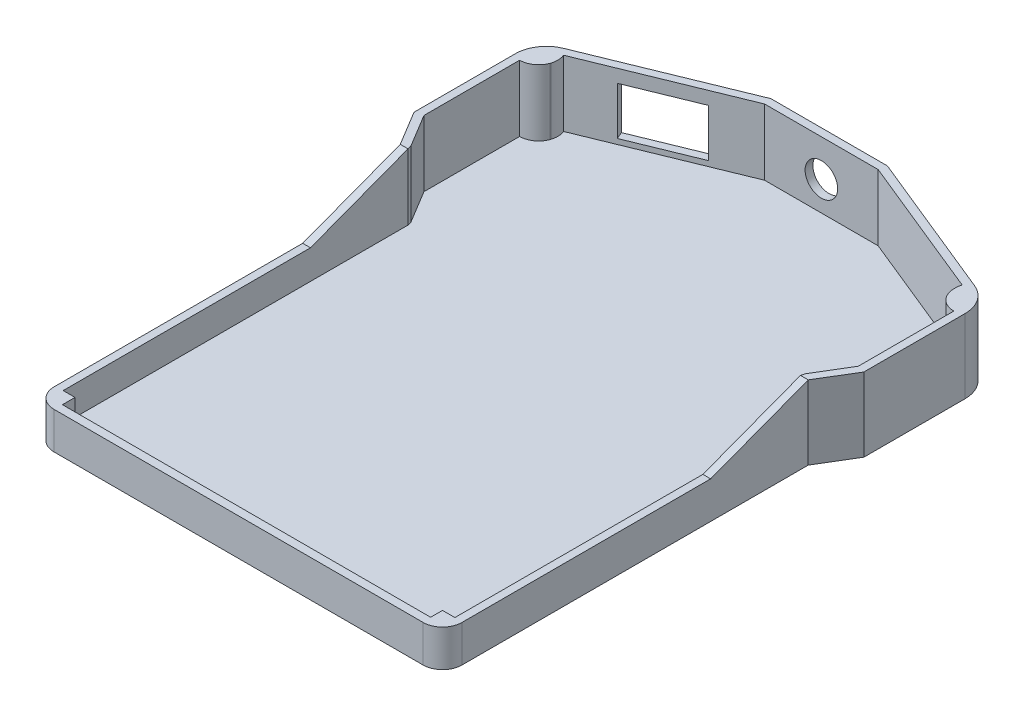
SolidWorks part; units mm, degrees
ref_plane "Front Plane" through (0, 0, 0) normal (0, 0, 1) x (1, 0, 0)
ref_plane "Top Plane" through (0, 0, 0) normal (0, 1, 0) x (1, 0, 0)
ref_plane "Right Plane" through (0, 0, 0) normal (1, 0, 0) x (0, 0, -1)
sketch "Sketch2" plane through (0, 0, 0) normal (0, 1, 0) x (1, 0, 0)
  line L0 (-52.5, 18.1181) -> (52.5, 18.1181)
  line L1 (-15, 76) -> (15, 76)
  line L2 (-52.5, 18.1181) -> (-52.5, -76)
  line L3 (-52.5, -76) -> (52.5, -76)
  line L4 (52.5, -7) -> (-52.5, -7)
  line L5 (52.5, 18.1181) -> (52.5, -76)
  line L8 (0, -76) -> (15, -76) construction
  line L11 (15, 76) -> (57.8941, 58.4854)
  line L12 (57.8941, 58.4854) -> (57.8941, 27.0518)
  line L13 (57.8941, 27.0518) -> (52.5, 18.1181)
  line L14 (-57.8941, 27.0518) -> (-52.5, 18.1181)
  line L15 (-57.8941, 58.4854) -> (-57.8941, 27.0518)
  line L16 (-15, 76) -> (-57.8941, 58.4854)
  point P0 (0, 0)
  dimension "D1" = 105
  dimension "D2" = 69
  dimension "D3" = 15
extrude "Boss-Extrude2" add sketch "Sketch2" along normal blind 19 contours L1 L16 L15 L14 L0 L13 L12 L11 | L5 L4 L2 L3 | L5 L0 L2 L4
sketch "Sketch4" plane through (52.5, 0, 0) normal (1, 0, 0) x (0, 0, -1)
  line L0 (-7, 9.5) -> (-76, 9.5) construction
  line L2 (-76, 19) -> (-76, 0) construction
  line L3 (-76, 9.5) -> (-7, 9.5)
  line L4 (-7, 9.5) -> (18.1181, 19)
  line L5 (18.1181, 19) -> (-76, 19)
  line L6 (-76, 19) -> (-76, 9.5)
  line L9 (-76, 0) -> (18.1181, 0)
  line L10 (18.1181, 0) -> (18.1181, 19)
  line L11 (18.1181, 19) -> (-76, 19)
  line L12 (-76, 19) -> (-76, 0)
  line L13 (-76, 0) -> (18.1181, 0)
  line L14 (18.1181, 0) -> (18.1181, 19)
  line L16 (-76, 9.5) -> (-76, 0)
  line M5 (18.1181, 19) -> (-76, 19)
  line M6 (-76, 19) -> (-76, 0)
  dimension "D1" = 69
  dimension "D2" = 9.5
  dimension "D3" = 0
extrude "Cut-Extrude13" cut sketch "Sketch4" against normal blind 119 contours L3 L4 M5 M6
sketch "Sketch5" plane through (0, 19, 0) normal (0, 1, 0) x (1, 0, 0)
  line L0 (-14.6074, 74) -> (14.6074, 74)
  line L5 (14.244, 74.1484) -> (57.1381, 56.6338)
  line L6 (14.6074, 74) -> (55.8941, 57.1417)
  line L8 (55.8941, 58.4854) -> (55.8941, 27.0518)
  line L9 (55.8941, 57.1417) -> (55.8941, 27.6088)
  line L10 (-56.182, 28.0856) -> (-50.7879, 19.1519)
  line L11 (-55.8941, 27.6088) -> (-50.7879, 19.1519)
  line L12 (56.182, 28.0856) -> (50.7879, 19.1519)
  line L13 (55.8941, 27.6088) -> (50.7879, 19.1519)
  line L15 (-50.5, -7) -> (-50.5, 18.1181)
  line L16 (-14.244, 74.1484) -> (-57.1381, 56.6338)
  line L17 (-14.6074, 74) -> (-55.8941, 57.1417)
  line L18 (-50.5, -7) -> (-50.5, 18.1181)
  line L19 (-55.8941, 58.4854) -> (-55.8941, 27.0518)
  line L20 (-55.8941, 57.1417) -> (-55.8941, 27.6088)
  line L22 (-50.5, -76) -> (-50.5, -7)
  line L23 (-50.5, -74) -> (-50.5, -7)
  line L25 (50.5, -7) -> (50.5, 18.1181)
  line L26 (50.5, -7) -> (50.5, 18.1181)
  line L28 (50.5, -76) -> (50.5, -7)
  line L29 (50.5, -74) -> (50.5, -7)
  line L30 (-50.7879, 19.1519) -> (-50.5, 18.1181)
  line L31 (-52.5, -74) -> (52.5, -74)
  line L32 (-50.5, -74) -> (50.5, -74)
  line L33 (50.7879, 19.1519) -> (50.5, 18.1181)
  line L34 (-50.5, 18.1181) -> (50.5, 18.1181)
  line M15 (-52.5, 18.1181) -> (52.5, 18.1181)
  dimension "D2" = 2
  dimension "D3" = 2
  dimension "D4" = 2
  dimension "D5" = 2
  dimension "D6" = 2
  dimension "D7" = 2
  dimension "D8" = 2
  dimension "D9" = 2
  dimension "D10" = 2
  dimension "D11" = 2
  dimension "D12" = 2
extrude "Cut-Extrude15" cut sketch "Sketch5" against normal blind 17 contours L33 L13 L9 L6 L0 L17 L20 L11 L30 M15
sketch "Sketch7" plane through (0, 0, -18.1181) normal (0, 0, -1) x (-1, 0, 0)
  line L0 (50.5, 19) -> (50.5, 2)
  line L1 (50.5, 2) -> (11.5454, 2)
  line L2 (50.5, 2) -> (-50.5, 2) construction
  line L3 (11.5454, 2) -> (-50.5, 2)
  line L4 (-50.5, 2) -> (-50.5, 19)
  line L5 (-50.5, 19) -> (50.5, 19)
extrude "Cut-Extrude17" cut sketch "Sketch7" against normal blind 92
sketch "Sketch8" plane through (0, 0, -76) normal (0, 0, -1) x (-1, 0, 0)
  line L0 (-15, 19) -> (15, 0) construction
  line L1 (15, 0) -> (15, 19) construction
  line L2 (15, 19) -> (-15, 0) construction
  circle A0 centre (0, 9.5) radius 4.1862
extrude "Cut-Extrude18" cut sketch "Sketch8" against normal blind 92
sketch "Sketch11" plane through (0, 2, 0) normal (0, 1, 0) x (1, 0, 0)
  line L0 (-55.8941, 57.1417) -> (-51.3477, 58.9981)
  line L1 (-14.6074, 74) -> (-55.8941, 57.1417) construction
  line L2 (-51.3477, 58.9981) -> (-55.8941, 57.1417)
  line L3 (-55.8941, 57.1417) -> (-51.3477, 58.9981)
  line L4 (-55.8941, 57.1417) -> (-55.8941, 52.2309)
  line L5 (-51.3041, 55.3959) -> (-51.234, 55.5927)
  line L6 (-55.8941, 57.1417) -> (-55.8941, 52.2309)
  arc A0 (-51.3041, 55.3959) -> (-55.8941, 52.2309) centre (-55.8941, 57.1417) cw
  arc A1 (-51.3477, 58.9981) -> (-51.234, 55.5927) centre (-55.8941, 57.1417) cw
  line M6 (-14.6074, 74) -> (-55.8941, 57.1417)
  line M7 (-55.8941, 57.1417) -> (-55.8941, 27.6088)
extrude "Boss-Extrude3" add sketch "Sketch11" along normal blind 17 contours A1 A0 L5 M6 M7
sketch "Sketch12" plane through (0, 2, 0) normal (0, 1, 0) x (1, 0, 0)
  line L0 (55.8941, 57.1417) -> (55.8941, 27.6088) construction
  line L1 (14.6074, 74) -> (55.8941, 57.1417) construction
  line L2 (50.9424, 58.2985) -> (50.9424, 57.1417)
  line L3 (51.1864, 59.064) -> (55.8941, 57.1417)
  line L4 (55.8941, 57.1417) -> (55.8941, 52.19)
  arc A0 (50.9424, 57.1417) -> (55.8941, 52.19) centre (55.8941, 57.1417) ccw
  arc A1 (50.9424, 58.2985) -> (51.1864, 59.064) centre (55.8941, 57.1417) cw
extrude "Boss-Extrude4" add sketch "Sketch12" along normal blind 17
sketch "Sketch13" plane through (0, 2, 0) normal (0, 1, 0) x (1, 0, 0)
  line L3 (50.5, -73.8819) -> (47.3144, -73.8819)
  line L4 (50.5, -73.8819) -> (50.5, -70.8194)
  line L5 (50.5, -70.8194) -> (47.3144, -70.8194)
  line L6 (47.3144, -73.8819) -> (47.3144, -70.8194)
extrude "Boss-Extrude6" add sketch "Sketch13" along normal blind 7.5
sketch "Sketch14" plane through (0, 2, 0) normal (0, 1, 0) x (1, 0, 0)
  line L1 (-50.5, -73.8819) -> (-47.4486, -73.8819)
  line L2 (-50.5, -73.8819) -> (-50.5, -70.6438)
  line L3 (-50.5, -70.6438) -> (-47.4486, -70.6438)
  line L4 (-47.4486, -73.8819) -> (-47.4486, -70.6438)
extrude "Boss-Extrude7" add sketch "Sketch14" along normal blind 7.5
sketch3d "3DSketch1" plane through (0, 0, 0) normal (0, 0, 1) x (1, 0, 0)
fillet "Fillet1" radius 5 1 edges at (-52.5, 4.75, 76)
fillet "Fillet2" radius 5 1 edges at (52.5, 4.75, 76)
fillet "Fillet5" radius 8 1 edges at (57.8941, 9.5, -58.4854)
fillet "Fillet6" radius 8 1 edges at (-57.8941, 9.5, -58.4854)
sketch "Sketch18" plane through (-28.7414, 0, -70.3891) normal (-0.378, 0, -0.9258) x (-0.9258, 0, 0.378)
  line L1 (26.1147, 19) -> (26.1147, 0) construction
  line L4 (-3.364, 15.65) -> (14.636, 15.65)
  line L5 (-3.364, 15.65) -> (-3.364, 3.35)
  line L6 (-3.364, 3.35) -> (14.636, 3.35)
  line L7 (14.636, 15.65) -> (14.636, 3.35)
  point P4 (5.636, 9.5)
  dimension "D1" = 18
  dimension "D2" = 12.3
extrude "Cut-Extrude19" cut sketch "Sketch18" against normal blind 15
